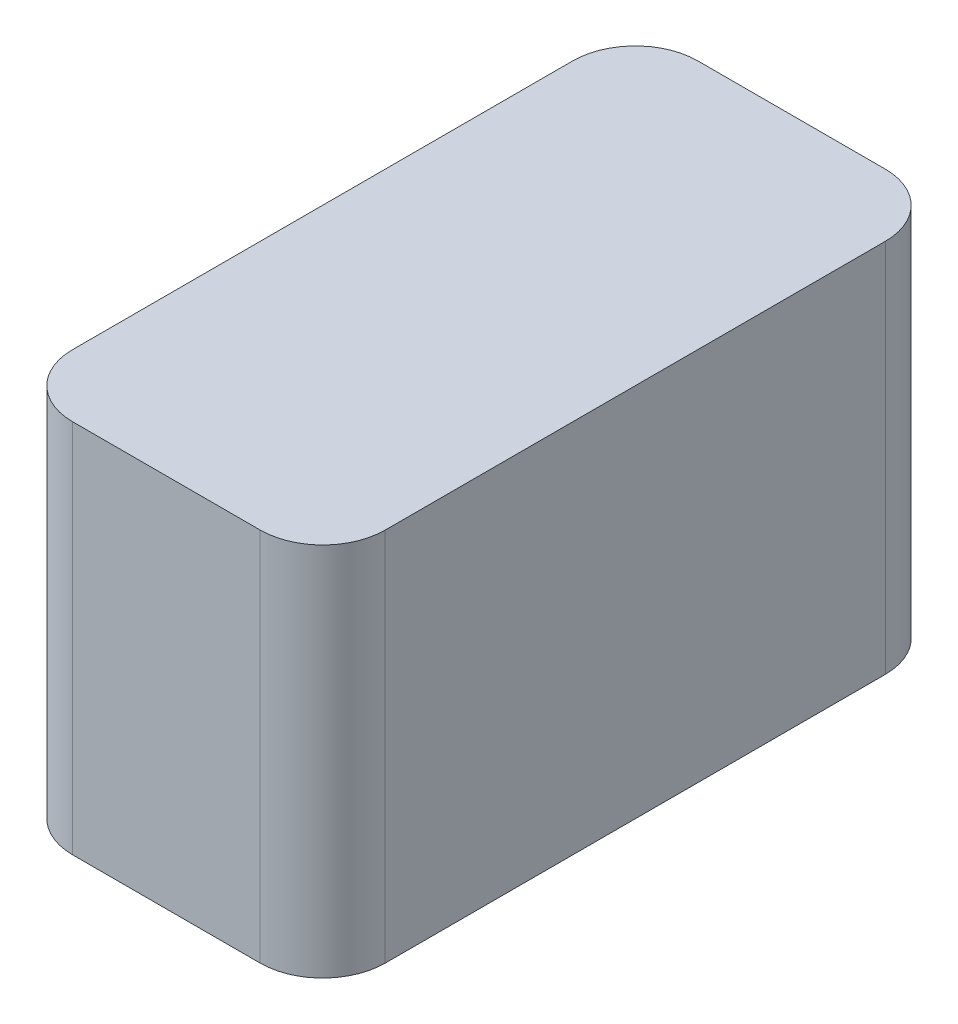
SolidWorks part; units mm, degrees
ref_plane "Front Plane" through (0, 0, 0) normal (0, 0, 1) x (1, 0, 0)
ref_plane "Top Plane" through (0, 0, 0) normal (0, 1, 0) x (1, 0, 0)
ref_plane "Right Plane" through (0, 0, 0) normal (1, 0, 0) x (0, 0, -1)
sketch "Sketch1" plane through (0, 0, 0) normal (0, 1, 0) x (1, 0, 0)
  line L0 (-2.5, 0) -> (2.5, 0) construction
  line L1 (-1.5, 5) -> (1.5, 5)
  line L2 (-2.5, 4) -> (-2.5, -4)
  line L3 (-1.5, -5) -> (1.5, -5)
  line L4 (2.5, 4) -> (2.5, -4)
  arc A0 (1.5, -5) -> (2.5, -4) centre (1.5, -4) ccw
  arc A1 (-2.5, -4) -> (-1.5, -5) centre (-1.5, -4) ccw
  arc A2 (-1.5, 5) -> (-2.5, 4) centre (-1.5, 4) ccw
  arc A3 (1.5, 5) -> (2.5, 4) centre (1.5, 4) cw
  point P9 (2.5, -5)
  point P14 (-2.5, 5)
  point P17 (2.5, 5)
  dimension "D3" = 1
  dimension "D1" = 10
  dimension "D2" = 5
extrude "Boss-Extrude1" add sketch "Sketch1" along normal blind 6
